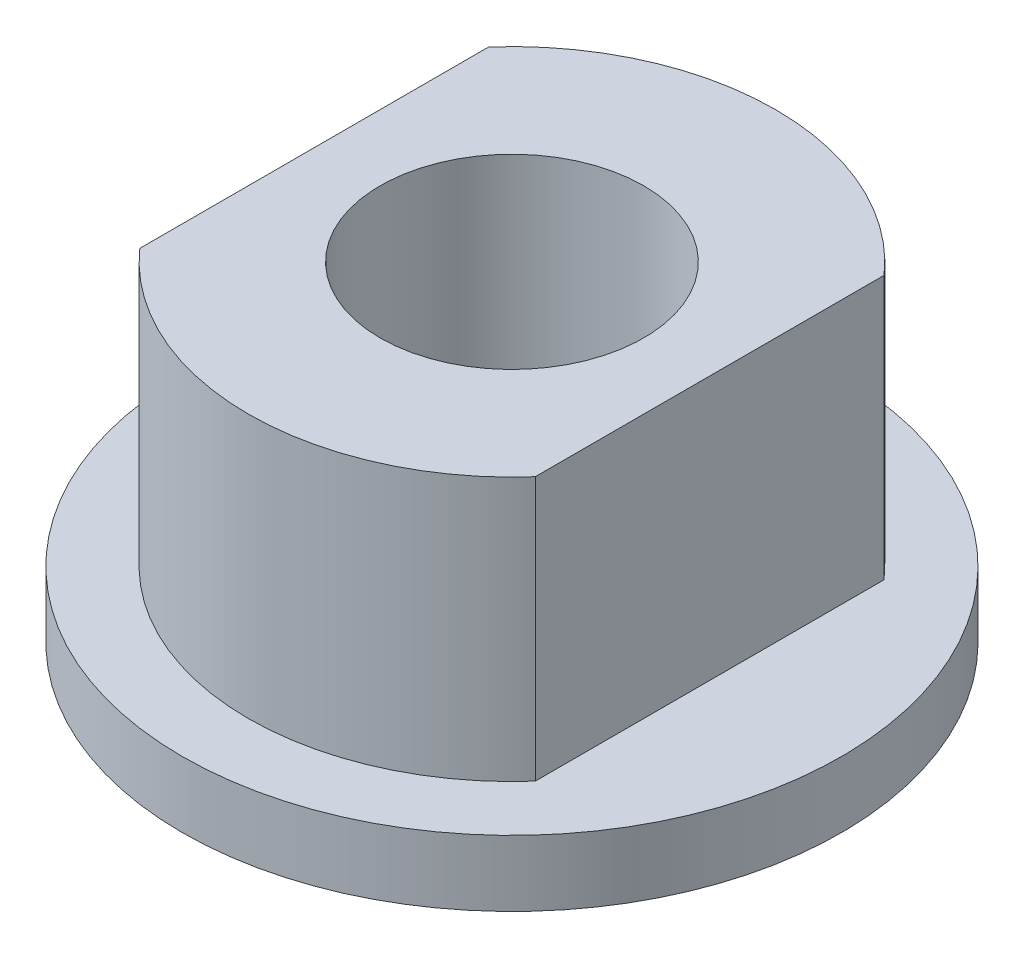
SolidWorks part; units mm, degrees
ref_plane "Alzado" through (0, 0, 0) normal (0, 0, 1) x (1, 0, 0)
ref_plane "Planta" through (0, 0, 0) normal (0, 1, 0) x (1, 0, 0)
ref_plane "Vista lateral" through (0, 0, 0) normal (1, 0, 0) x (0, 0, -1)
sketch "Croquis1" plane through (0, 0, 0) normal (0, 1, 0) x (1, 0, 0)
  circle A0 centre (0, 0) radius 12.5
  dimension "D1" = 25
extrude "Saliente-Extruir1" add sketch "Croquis1" along normal blind 2.5 contours A0
sketch "Croquis2" plane through (0, 2.5, 0) normal (0, 1, 0) x (1, 0, 0)
  line L0 (0, 14.9149) -> (0, -15.0823) construction
  line L1 (-7.5, 6.6144) -> (-7.5, -6.6144)
  line L2 (7.5, -6.6144) -> (7.5, 6.6144)
  arc A0 (-7.5, -6.6144) -> (7.5, -6.6144) centre (0, 0) ccw
  circle A1 centre (0, 0) radius 12.5 construction
  arc A2 (7.5, 6.6144) -> (-7.5, 6.6144) centre (0, 0) ccw
  dimension "D1" = 20
  dimension "D2" = 15
  dimension "D3" = 7.5
extrude "Saliente-Extruir2" add sketch "Croquis2" along normal blind 10 contours L2 A2 L1 A0
sketch "Croquis3" plane through (0, 12.5, 0) normal (0, 1, 0) x (1, 0, 0)
  circle A0 centre (0, 0) radius 5
  arc A1 (7.5, 6.6144) -> (-7.5, 6.6144) centre (0, 0) ccw construction
  arc A3 (-7.5, -6.6144) -> (7.5, -6.6144) centre (0, 0) ccw construction
  dimension "D1" = 10
extrude "Cortar-Extruir1" cut sketch "Croquis3" against normal through all contours A0
